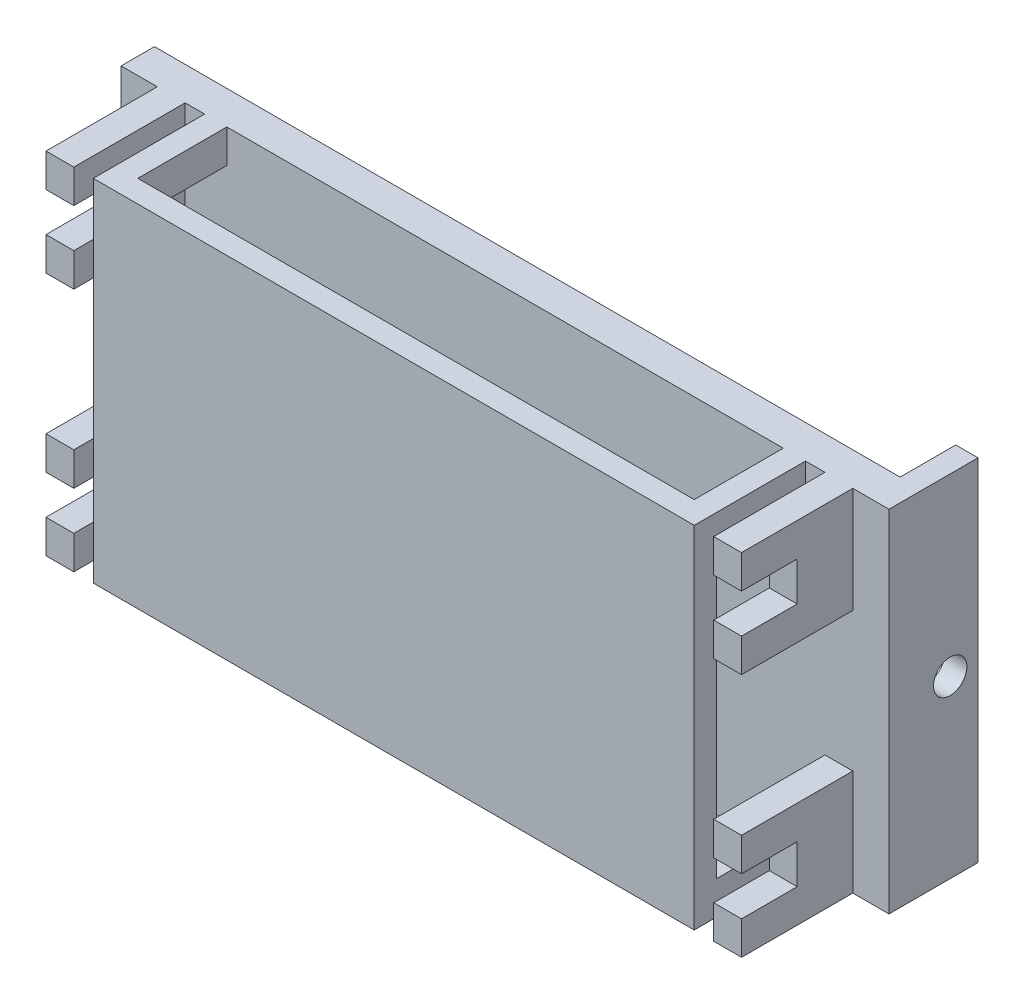
SolidWorks part; units mm, degrees
ref_plane "Plano frontal" through (0, 0, 0) normal (0, 0, 1) x (1, 0, 0)
ref_plane "Plano superior" through (0, 0, 0) normal (0, 1, 0) x (1, 0, 0)
ref_plane "Plano direito" through (0, 0, 0) normal (1, 0, 0) x (0, 0, -1)
sketch "Esboço1" plane through (0, 0, 0) normal (0, 0, 1) x (1, 0, 0)
  line L0 (0, -31.682) -> (0, -0.182)
  line L1 (0, -31.682) -> (-69, -31.682)
  line L3 (0, -0.182) -> (-69, -0.182)
  line L4 (-69, -31.682) -> (-69, -0.182)
  point P0 (0, 0)
  dimension "D1" = 31.5
  dimension "D2" = 69
extrude "Ressalto-extrusão1" add sketch "Esboço1" along normal blind 6
sketch "Esboço2" plane through (0, 0, 6) normal (0, 0, 1) x (1, 0, 0)
  line L0 (-69, -31.682) -> (0, -31.682) construction
  line L1 (-62.5, -31.682) -> (-57.5, -31.682)
  line L2 (-62.5, -31.682) -> (-62.5, -12.682)
  line L3 (-62.5, -12.682) -> (-57.5, -12.682)
  line L4 (-57.5, -31.682) -> (-57.5, -12.682)
  line L5 (-69, -0.182) -> (-69, -31.682) construction
  dimension "D1" = 19
  dimension "D2" = 5
  dimension "D3" = 6.5
extrude "Ressalto-extrusão2" add sketch "Esboço2" along normal blind 20
sketch "Esboço3" plane through (0, 0, 26) normal (0, 0, 1) x (1, 0, 0)
  line L0 (-57.5, -31.682) -> (-57.5, -12.682) construction
  line L1 (-57.5, -18.682) -> (-62.5, -18.682)
  line L2 (-57.5, -18.682) -> (-57.5, -25.682)
  line L3 (-57.5, -25.682) -> (-62.5, -25.682)
  line L4 (-62.5, -18.682) -> (-62.5, -25.682)
  line L5 (-62.5, -12.682) -> (-62.5, -31.682) construction
  line L6 (-57.5, -12.682) -> (-62.5, -12.682) construction
  line L7 (-62.5, -31.682) -> (-57.5, -31.682) construction
  dimension "D1" = 6
  dimension "D2" = 6
extrude "Corte-extrusão1" cut sketch "Esboço3" against normal blind 10
sketch "Esboço4" plane through (0, 0, 6) normal (0, 0, 1) x (1, 0, 0)
  line L0 (-57.5, -31.682) -> (0, -31.682) construction
  line L1 (-54, -31.682) -> (-50, -31.682)
  line L2 (-54, -31.682) -> (-54, -0.182)
  line L3 (-54, -0.182) -> (-50, -0.182)
  line L4 (-50, -31.682) -> (-50, -0.182)
  line L5 (0, -0.182) -> (-69, -0.182) construction
  line L6 (-57.5, -31.682) -> (-57.5, -12.682) construction
  dimension "D1" = 3.5
  dimension "D2" = 4
extrude "Ressalto-extrusão3" add sketch "Esboço4" along normal blind 20
sketch "Esboço5" plane through (-50, 0, 0) normal (1, 0, 0) x (0, 0, -1)
  line L1 (-22, -25.682) -> (-6, -25.682)
  line L2 (-22, -25.682) -> (-22, -6.182)
  line L5 (-26, -31.682) -> (-6, -31.682) construction
  line L6 (-22, -6.182) -> (-22, -0.182)
  line L7 (-26, -0.182) -> (-6, -0.182) construction
  line L8 (-22, -0.182) -> (-6, -0.182)
  line L10 (-26, -31.682) -> (-26, -0.182) construction
  line L12 (-6, -31.682) -> (-6, -0.182) construction
  line L13 (-6, -25.682) -> (-6, -0.182)
  dimension "D1" = 4
  dimension "D2" = 6
extrude "Corte-extrusão2" cut sketch "Esboço5" against normal up to surface (4 mm away) up to face at (-54, -15.932, 16)
sketch "Esboço6" plane through (-50, 0, 0) normal (1, 0, 0) x (0, 0, -1)
  line L1 (-26, -31.682) -> (-22, -31.682)
  line L2 (-26, -31.682) -> (-26, -25.682)
  line L3 (-26, -25.682) -> (-22, -25.682)
  line L4 (-22, -31.682) -> (-22, -25.682)
extrude "Ressalto-extrusão4" add sketch "Esboço6" along normal up to surface (50 mm away) up to face at (0, -15.932, 3)
ref_plane "Plano2" through (0, -0.182, 0) normal (0, 1, 0) x (1, 0, 0)
mirror "Espelhar10" about plane through (0, -0.182, 0) normal (0, 1, 0) of bodies 110 103
ref_plane "Plano1" through (0, 0, 0) normal (1, 0, 0) x (0, 0, -1)
mirror "Espelhar11" about plane through (0, 0, 0) normal (1, 0, 0) of bodies 106
sketch "Esboço7" plane through (0, 0, 0) normal (0, 0, -1) x (-1, 0, 0)
  line L0 (69, -31.682) -> (-69, -31.682) construction
  line L1 (-69, 31.318) -> (-65, 31.318)
  line L2 (-69, 31.318) -> (-69, -31.682)
  line L3 (-69, -31.682) -> (-65, -31.682)
  line L4 (-65, 31.318) -> (-65, -31.682)
  dimension "D1" = 4
extrude "Ressalto-extrusão5" add sketch "Esboço7" along normal blind 10
sketch "Esboço8" plane through (69, 0, 0) normal (1, 0, 0) x (0, 0, -1)
  line L0 (0, -31.682) -> (0, 31.318) construction
  line L1 (0, -31.682) -> (0, 31.318)
  line L3 (10, 31.318) -> (0, 31.318) construction
  line L4 (10, 31.318) -> (10, -31.682) construction
  line L5 (10, -31.682) -> (0, -31.682) construction
  line L6 (0, 31.318) -> (0, -31.682) construction
  circle A0 centre (5, -0.182) radius 3
  dimension "D1" = 6
extrude "Corte-extrusão3" cut sketch "Esboço8" against normal through all both and the other way through all contours A0
sketch "Esboço13" plane through (0, -25.682, 0) normal (0, 1, 0) x (1, 0, 0)
  line L1 (-50, -22) -> (50, -22)
  line L2 (-50, -22) -> (-50, -26)
  line L3 (-50, -26) -> (50, -26)
  line L4 (50, -22) -> (50, -26)
extrude "Ressalto-extrusão6" add sketch "Esboço13" along normal blind 53
